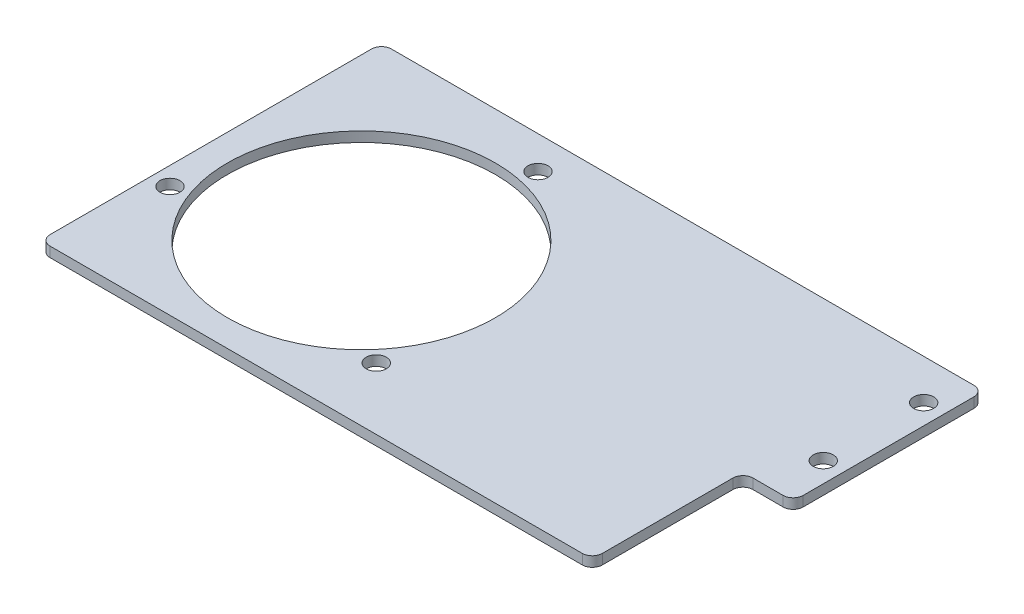
SolidWorks part; units mm, degrees
ref_plane "Front Plane" through (0, 0, 0) normal (0, 0, 1) x (1, 0, 0)
ref_plane "Top Plane" through (0, 0, 0) normal (0, 1, 0) x (1, 0, 0)
ref_plane "Right Plane" through (0, 0, 0) normal (1, 0, 0) x (0, 0, -1)
sketch "Sketch1" plane through (0, 0, 0) normal (0, 1, 0) x (1, 0, 0)
  line L0 (0, 114.3) -> (0, -101.6) construction
  line L1 (273.05, 114.3) -> (-95.25, 114.3)
  line L2 (279.4, 107.95) -> (279.4, 0)
  line L3 (241.3, -101.6) -> (-95.25, -101.6)
  line L4 (-101.6, 107.95) -> (-101.6, -95.25)
  line L5 (254, -6.35) -> (273.05, -6.35)
  line L6 (266.7, 0) -> (266.7, 114.3) construction
  line L7 (-101.6, 0) -> (285.75, 0) construction
  line L8 (0, 0) -> (-101.6, -34.9837) construction
  line L11 (247.65, -95.25) -> (247.65, -12.7)
  circle A0 centre (0, 0) radius 84.7725
  circle A1 centre (0, 0) radius 95.25 construction
  circle A2 centre (-90.0606, -31.0104) radius 6.35
  arc A3 (247.65, -12.7) -> (254, -6.35) centre (254, -12.7) cw
  arc A4 (-95.25, 114.3) -> (-101.6, 107.95) centre (-95.25, 107.95) ccw
  circle A5 centre (18.1746, 93.5) radius 6.35
  circle A6 centre (71.8861, -62.4896) radius 6.35
  arc A7 (-95.25, -101.6) -> (-101.6, -95.25) centre (-95.25, -95.25) cw
  arc A8 (241.3, -101.6) -> (247.65, -95.25) centre (241.3, -95.25) ccw
  arc A9 (273.05, -6.35) -> (279.4, 0) centre (273.05, 0) ccw
  arc A10 (273.05, 114.3) -> (279.4, 107.95) centre (273.05, 107.95) cw
  circle A11 centre (266.7, 88.9) radius 6.35
  circle A12 centre (266.7, 25.4) radius 6.35
  point P0 (0, 0)
  point P11 (0, 0)
  point P21 (247.65, -6.35)
  point P32 (247.65, -101.6)
  point P46 (0, 0)
  dimension "D3" = 169.545
  dimension "D5" = 190.5
  dimension "D6" = 12.7
  dimension "D7" = 114.3
  dimension "D8" = 279.4
  dimension "D11" = 6.35
  dimension "D14" = 12.7
  dimension "D1" = 101.6
  dimension "D2" = 101.6
  dimension "D4" = 19
  dimension "D9" = 95.25
  dimension "D10" = 31.75
  dimension "D13" = 12.7
  dimension "D15" = 25.4
extrude "Boss-Extrude1" add sketch "Sketch1" along normal blind 6.35
sketch "Sketch2" plane through (0, 0, 0) normal (0, -1, 0) x (1, 0, 0)
  line L0 (-101.6, -107.95) -> (-101.6, 95.25) construction
  line L1 (273.05, -114.3) -> (-95.25, -114.3) construction
  line L2 (279.4, 0) -> (279.4, -107.95) construction
  line L3 (-95.25, 101.6) -> (241.3, 101.6) construction
  line L4 (-101.6, -107.95) -> (-101.6, 95.25)
  line L5 (273.05, -114.3) -> (-95.25, -114.3)
  line L6 (279.4, 0) -> (279.4, -107.95)
  line L7 (-95.25, 101.6) -> (241.3, 101.6)
  line L8 (88.9, -114.3) -> (88.9, 101.6) construction
  line L9 (-101.6, -6.35) -> (279.4, -6.35) construction
  line L11 (333.375, 146.05) -> (-155.575, 146.05)
  line L12 (333.375, 146.05) -> (333.375, -158.75)
  line L13 (333.375, -158.75) -> (-155.575, -158.75)
  line L14 (-155.575, 146.05) -> (-155.575, -158.75)
  line L15 (333.375, 146.05) -> (-155.575, -158.75) construction
  line L16 (333.375, -158.75) -> (-155.575, 146.05) construction
  point P12 (88.9, -6.35)
  dimension "D1" = 381
  dimension "D2" = 215.9
  dimension "D3" = 488.95
  dimension "D4" = 304.8
sketch "Sketch3" plane through (0, 6.35, 0) normal (0, 1, 0) x (1, 0, 0)
  circle A0 centre (0, 0) radius 84.7725 construction
  point P0 (84.7725, 0)
